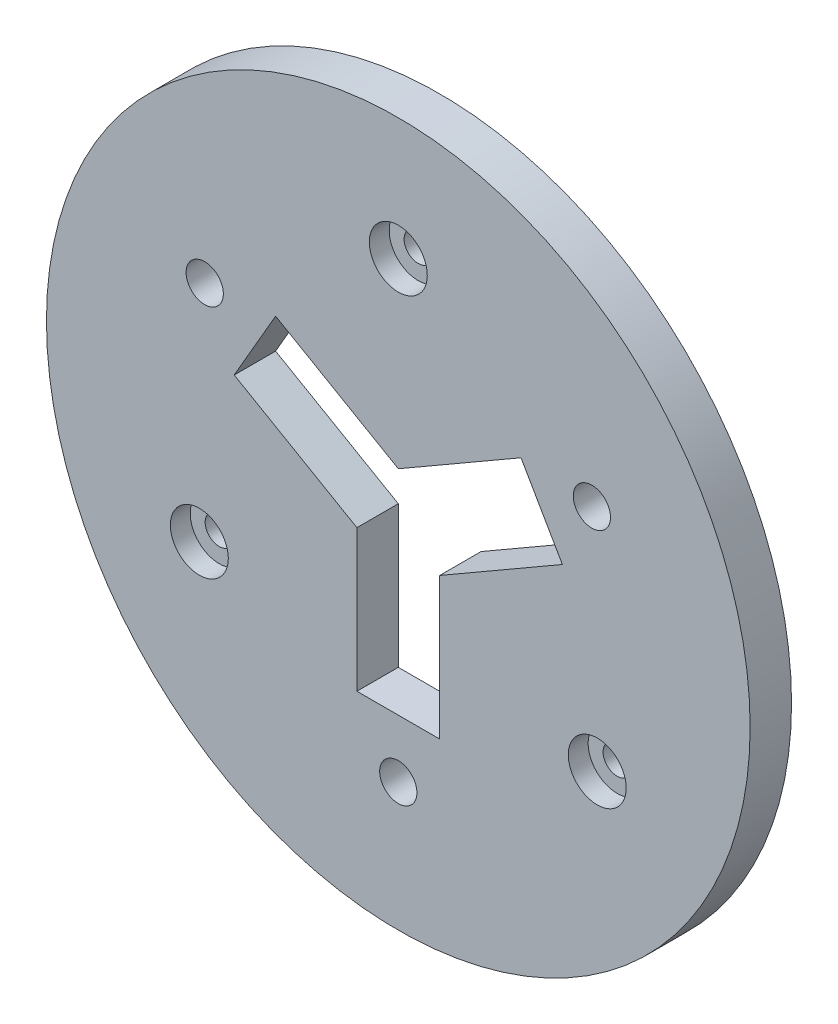
SolidWorks part; units mm, degrees
material "7075-O (SS)"
ref_plane "Front" through (0, 0, 0) normal (0, 0, 1) x (1, 0, 0)
ref_plane "Top" through (0, 0, 0) normal (0, 1, 0) x (1, 0, 0)
ref_plane "Right" through (0, 0, 0) normal (1, 0, 0) x (0, 0, -1)
sketch "Croquis1" plane through (0, 0, 0) normal (0, 0, 1) x (1, 0, 0)
  circle A0 centre (0, 0) radius 42.5
  dimension "D1" = 85
extrude "Saliente-Extruir1" add sketch "Croquis1" along normal mid plane 5
hole_wizard "Refrentado para tornillo con cabeza troncocónica de M31" positions "Croquis2" profile "Croquis4" counterbore size "M3" standard "Ansi Metric" end condition up to next
sketch "Croquis2" plane through (0, 0, 2.5) normal (0, 0, 1) x (1, 0, 0)
  line L0 (0, -2.75) -> (0, 2.75) construction
  line L1 (2.75, 0) -> (-2.75, 0) construction
  point P0 (0, 27.75)
  point P12 (24.0322, -13.875)
  point P13 (-24.0322, -13.875)
  dimension "D1" = 27.75
  dimension "D2" = 3
sketch "Croquis4" plane through (0, 27.75, 2.5) normal (1, 0, 0) x (0, -1, 0)
  line L0 (0, 0) -> (0, 5)
  line L1 (0, 5) -> (1.7, 5)
  line L3 (1.7, 5) -> (1.7, 2.4)
  line L4 (1.7, 2.4) -> (3.5, 2.4)
  line L5 (3.5, 2.4) -> (3.5, 0)
  line L7 (3.5, 0) -> (0, 0)
  line L11 (0, -6.35) -> (0, 107.95) construction
  dimension "Diámetro de taladro hasta el siguiente" = 3.4
  dimension "Profundidad de taladro hasta el siguiente" = 5
  dimension "Diámetro de refrentado" = 7
  dimension "Profundidad de refrentado" = 2.4
hole_wizard "Taladro de margen para M41" positions "Croquis5" profile "Croquis7" hole size "M4" standard "Ansi Metric" end condition up to next
sketch "Croquis5" plane through (0, 0, 2.5) normal (0, 0, 1) x (1, 0, 0)
  line L0 (0, -2.75) -> (0, 2.75) construction
  line L1 (2.75, 0) -> (-2.75, 0) construction
  point P0 (0, -27)
  point P12 (-23.3827, 13.5)
  point P13 (23.3827, 13.5)
  dimension "D1" = 27
  dimension "D2" = 3
sketch "Croquis7" plane through (0, -27, 2.5) normal (1, 0, 0) x (0, -1, 0)
  line L0 (0, 0) -> (0, 5)
  line L1 (0, 5) -> (2.25, 5)
  line L2 (2.25, 5) -> (2.25, 0)
  line L5 (2.25, 0) -> (0, 0)
  line L11 (0, -6.35) -> (0, 107.95) construction
  dimension "Diámetro de taladro hasta el siguiente" = 4.5
  dimension "Profundidad de taladro hasta el siguiente" = 5
sketch "Croquis8" plane through (0, 0, 2.5) normal (0, 0, 1) x (1, 0, 0)
  line L0 (0, 0) -> (0, -20) construction
  line L1 (0, -2.75) -> (0, 2.75) construction
  line L2 (-17.3205, 10) -> (0, 0) construction
  line L3 (0, 0) -> (17.3205, 10) construction
  line L4 (-14.8205, 14.3301) -> (0, 5.7735)
  line L5 (0, 5.7735) -> (14.8205, 14.3301)
  line L6 (5, -2.8868) -> (5, -20)
  line L7 (-19.8205, 5.6699) -> (-5, -2.8868)
  line L8 (5, -2.8868) -> (19.8205, 5.6699)
  line L9 (-5, -2.8868) -> (-5, -20)
  line L10 (14.8205, 14.3301) -> (19.8205, 5.6699)
  line L11 (-14.8205, 14.3301) -> (-19.8205, 5.6699)
  line L12 (-5, -20) -> (5, -20)
  line L13 (-2.5, 4.3301) -> (14.8205, 14.3301) construction
  line L14 (-14.8205, 14.3301) -> (2.5, 4.3301) construction
  line L15 (-19.8205, 5.6699) -> (-2.5, -4.3301) construction
  line L16 (-5, 0) -> (-5, -20) construction
  line L17 (2.5, -4.3301) -> (19.8205, 5.6699) construction
  line L18 (5, 0) -> (5, -20) construction
  dimension "D1" = 120
  dimension "D2" = 120
  dimension "D3" = 20
  dimension "D4" = 5
  dimension "D5" = 5
extrude "Cortar-Extruir1" cut sketch "Croquis8" against normal up to next
